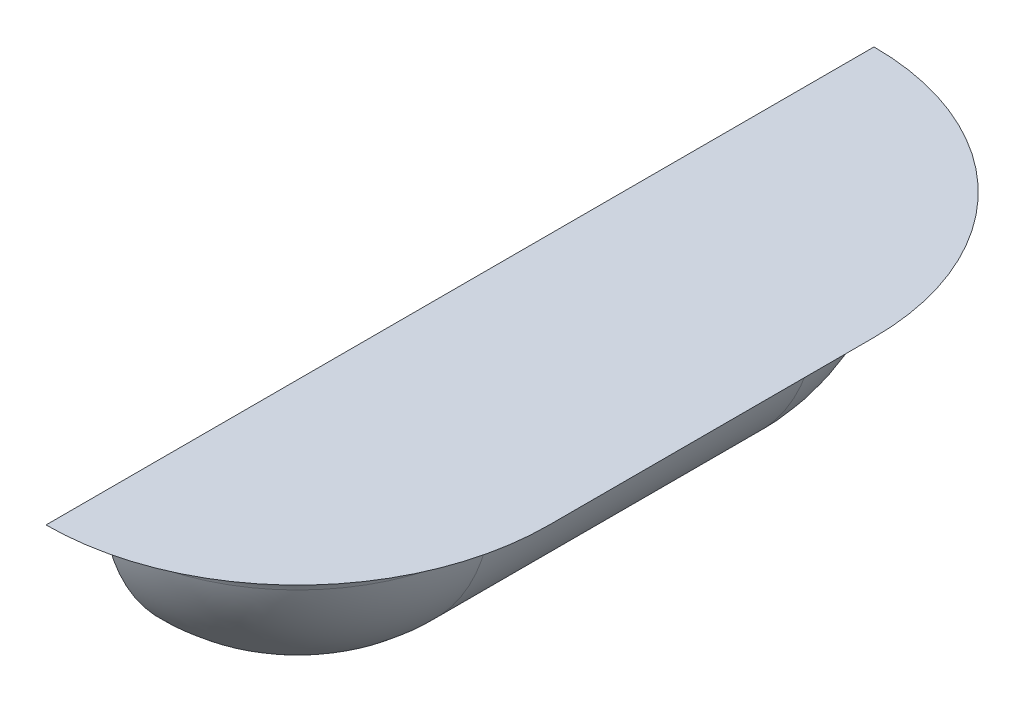
SolidWorks part; units mm, degrees
ref_plane "Plane1" through (0, 0, 0) normal (0, 0, 1) x (1, 0, 0)
ref_plane "Plane2" through (0, 0, 0) normal (0, 1, 0) x (1, 0, 0)
ref_plane "Plane3" through (0, 0, 0) normal (1, 0, 0) x (0, 0, -1)
sketch "Sketch1" plane through (0, 0, 0) normal (0, 0, 1) x (1, 0, 0)
  line L0 (-15, 0) -> (15, 0)
  line L1 (-15, 0) -> (-15, 3.4642)
  line L2 (15, 3.4642) -> (-15, 3.4642)
  line L3 (15, 3.4642) -> (15, 0)
  line L4 (0, 0) -> (0, 3.4642) construction
  line L5 (50, 0) -> (-50, 0) construction
  dimension "D1" = 30
extrude "Base-Extrude" add sketch "Sketch1" along normal mid plane 50
sketch "Layout Sketch" plane through (0, 0, 0) normal (0, -1, 0) x (1, 0, 0)
  line L0 (-6.5173, 0) -> (7.2244, 0) construction
  line L1 (11.2638, 0) -> (-11.2638, 0) construction
  line L2 (0, 9.1132) -> (0, -7.6236) construction
  line L3 (0, -50) -> (0, 50) construction
  line L9 (-3, -16) -> (-3, 16)
  line L11 (3, 10) -> (3, -10)
  arc A0 (3, 10) -> (-3, 16) centre (-3, 10) ccw
  arc A1 (3, -10) -> (-3, -16) centre (-3, -10) cw
  dimension "Overall width" = 32
  dimension "Depth" = 6
sketch "Louver Body" plane through (0, 0, 0) normal (0, 0, 1) x (1, 0, 0)
  line L0 (-3, 0) -> (-3, -6)
  line L1 (-15, 0) -> (15, 0) construction
  line L2 (-3, 0) -> (3, 0)
  line L4 (3, 0) -> (3, 3.4642) construction
  line L5 (15, 3.4642) -> (-15, 3.4642) construction
  line L6 (-3, -6) -> (-3.0249, -6) construction
  line L8 (0, 3.4642) -> (0, 0) construction
  arc A0 (-3, -6) -> (3, 0) centre (-3, 0) ccw
extrude "Boss-Extrude1" add sketch "Louver Body" along normal mid plane 10
sketch "Sketch12" plane through (0, 0, 5) normal (0, 0, 1) x (1, 0, 0)
  line L0 (-3, 0) -> (-3, -6) construction
  line L1 (-3, 0) -> (-3, -6) construction
  line L2 (-15, 0) -> (15, 0) construction
  line L5 (3, 0) -> (-3, 0)
  line L6 (-3, 0) -> (-3, -6)
  line L7 (3, 0) -> (-3, 0)
  line L8 (-3, 0) -> (-3, -6)
  arc A0 (-3, -6) -> (3, 0) centre (-3, 0) ccw construction
  arc A2 (-3, -6) -> (3, 0) centre (-3, 0) ccw
  arc A3 (-3, -6) -> (3, 0) centre (-3, 0) ccw
  dimension "D1" = 0
revolve "Boss-Revolve2" add sketch "Sketch12" angle 90 about L1
sketch "Sketch13" plane through (0, 0, -5) normal (0, 0, -1) x (-1, 0, 0)
  line L0 (3, -6) -> (3, 0) construction
  line L1 (15, 0) -> (-15, 0) construction
  line L2 (3, 0) -> (-3, 0)
  line L3 (3, -6) -> (3, 0)
  line L4 (3, 0) -> (-3, 0)
  line L5 (3, -6) -> (3, 0)
  arc A1 (-3, 0) -> (3, -6) centre (3, 0) ccw
  arc A2 (-3, 0) -> (3, -6) centre (3, 0) ccw
  dimension "D1" = 0
revolve "Boss-Revolve3" add sketch "Sketch13" angle 90 about L0
fillet "Fillet1" radius 2 3 edges at (1.2426, 0, 9.2426) (3, 0, 0) (1.2426, 0, -9.2426)
sketch "Sketch8" plane through (-15, 0, 0) normal (-1, 0, 0) x (0, 0, 1)
  line L4 (-25, 0) -> (25, 0)
  line L5 (25, 0) -> (25, 3.4642)
  line L6 (25, 3.4642) -> (-25, 3.4642)
  line L7 (-25, 3.4642) -> (-25, 0)
  line L8 (-25, 0) -> (25, 0)
  line L9 (25, 0) -> (25, 3.4642)
  line L10 (25, 3.4642) -> (-25, 3.4642)
  line L11 (-25, 3.4642) -> (-25, 0)
  dimension "D1" = 0
extrude "Cut-Extrude4" cut sketch "Sketch8" against normal through all
sketch "Orientation sketch" plane through (0, 0, 0) normal (0, 1, 0) x (-1, 0, 0)
  line L2 (3, 12.746) -> (3, -12.746)
  line L3 (3, 12.746) -> (3, -12.746)
  line L4 (-4.746, 5) -> (-4.746, -5)
  line L5 (-4.746, 5) -> (-4.746, -5)
  arc A2 (3, 12.746) -> (-4.746, 5) centre (3, 5) ccw
  arc A3 (3, 12.746) -> (-4.746, 5) centre (3, 5) ccw
  arc A4 (-4.746, -5) -> (3, -12.746) centre (3, -5) ccw
  arc A5 (-4.746, -5) -> (3, -12.746) centre (3, -5) ccw
  dimension "D1" = 0
scale "Scale1" [suppressed]
